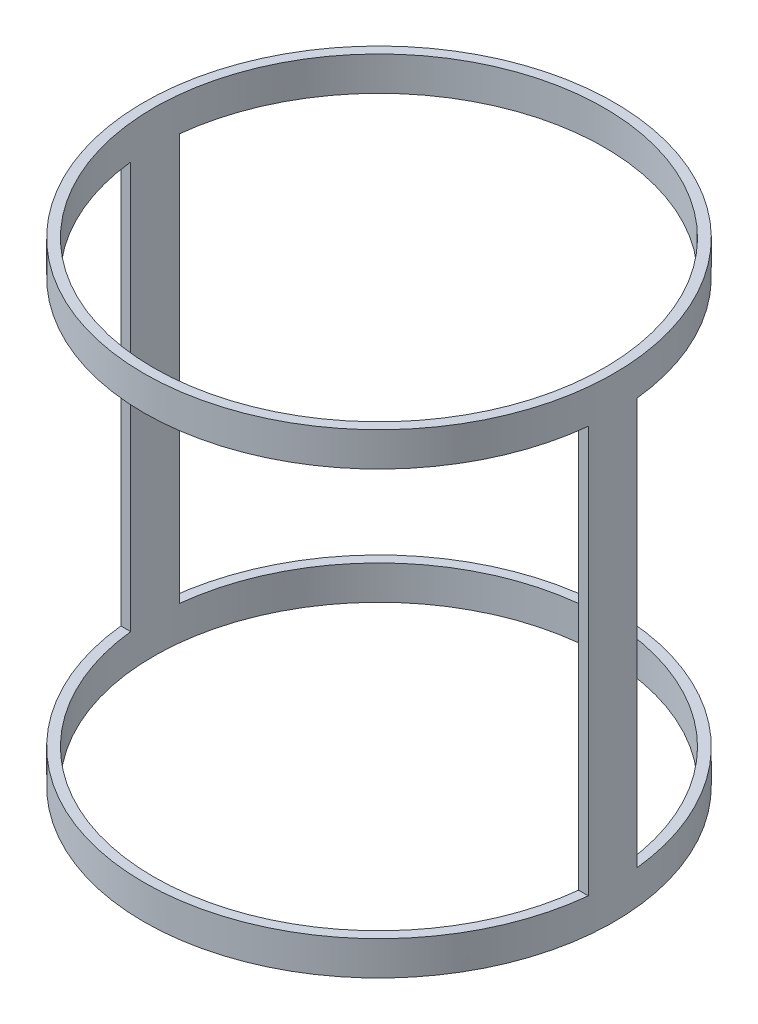
SolidWorks part; units mm, degrees
ref_plane "Front Plane" through (0, 0, 0) normal (0, 0, 1) x (1, 0, 0)
ref_plane "Top Plane" through (0, 0, 0) normal (0, 1, 0) x (1, 0, 0)
ref_plane "Right Plane" through (0, 0, 0) normal (1, 0, 0) x (0, 0, -1)
sketch "Sketch1" plane through (0, 0, 0) normal (0, 1, 0) x (1, 0, 0)
  line L0 (-47.9902, 5) -> (-45.9789, 5)
  line L2 (47.9902, -5) -> (45.9789, -5)
  line L4 (-45.9789, -5) -> (-47.9902, -5)
  line L5 (45.9789, 5) -> (47.9902, 5)
  arc A0 (-47.9902, 5) -> (-47.9902, -5) centre (0, 0) ccw
  arc A1 (-45.9789, 5) -> (-45.9789, -5) centre (0, 0) ccw
  arc A2 (45.9789, -5) -> (45.9789, 5) centre (0, 0) ccw
  arc A3 (47.9902, -5) -> (47.9902, 5) centre (0, 0) ccw
  dimension "D1" = 96.5
  dimension "D2" = 92.5
  dimension "D3" = 5
  dimension "D4" = 5
extrude "Boss-Extrude1" add sketch "Sketch1" along normal blind 97.5
sketch "Sketch2" plane through (0, 0, 0) normal (0, 1, 0) x (1, 0, 0)
  circle A0 centre (0, 0) radius 48.25
  circle A1 centre (0, 0) radius 46.25
extrude "Boss-Extrude2" add sketch "Sketch2" along normal blind 7
sketch "Sketch3" plane through (0, 97.5, 0) normal (0, 1, 0) x (1, 0, 0)
  circle A0 centre (0, 0) radius 48.25
  circle A1 centre (0, 0) radius 46.25
extrude "Boss-Extrude3" add sketch "Sketch3" against normal blind 7
